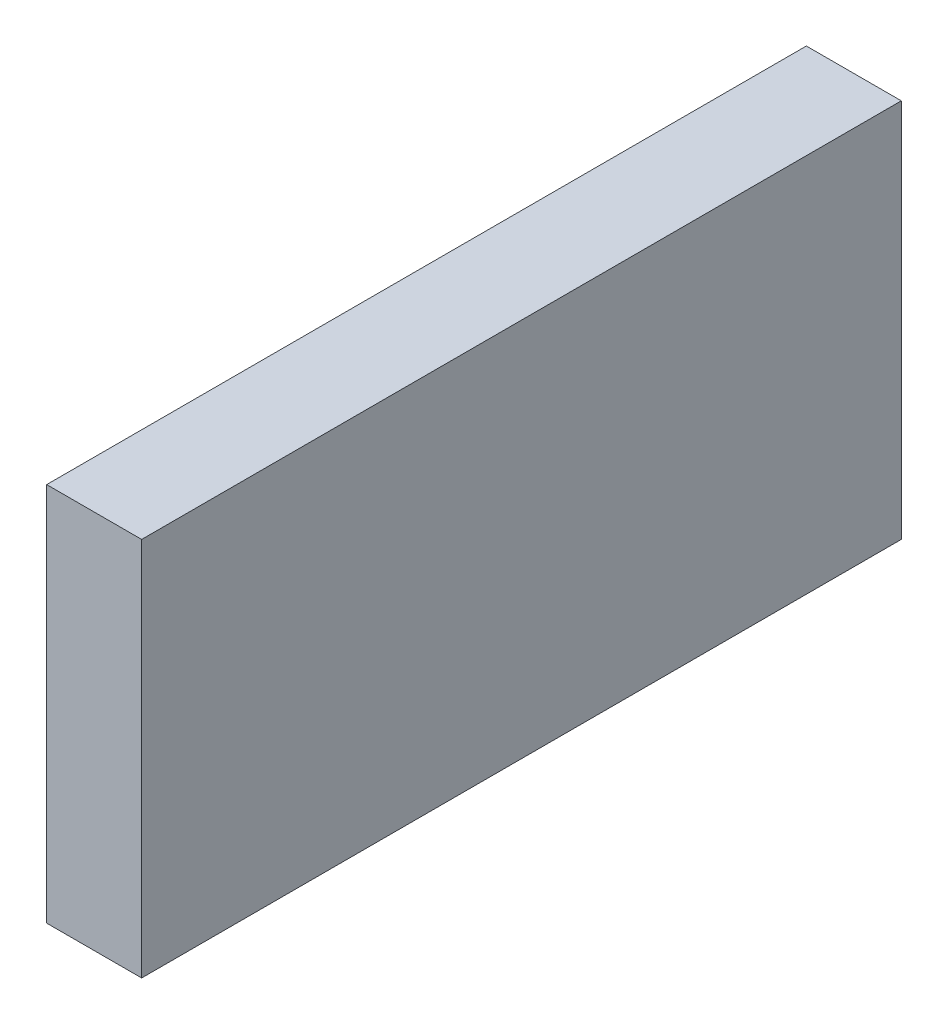
SolidWorks part; units mm, degrees
ref_plane "Front Plane" through (0, 0, 0) normal (0, 0, 1) x (1, 0, 0)
ref_plane "Top Plane" through (0, 0, 0) normal (0, 1, 0) x (1, 0, 0)
ref_plane "Right Plane" through (0, 0, 0) normal (1, 0, 0) x (0, 0, -1)
sketch "Sketch2" plane through (0, 0, 0) normal (0, 1, 0) x (1, 0, 0)
  line L0 (-1.4776, 3.3954) -> (-1.4776, -8.6046)
  line L1 (-1.4776, -8.6046) -> (0.0224, -8.6046)
  line L2 (0.0224, -8.6046) -> (0.0224, 3.3954)
  line L3 (0.0224, 3.3954) -> (-1.4776, 3.3954)
  dimension "D1" = 1.5
  dimension "D2" = 12
extrude "Boss-Extrude1" add sketch "Sketch2" along normal blind 6
